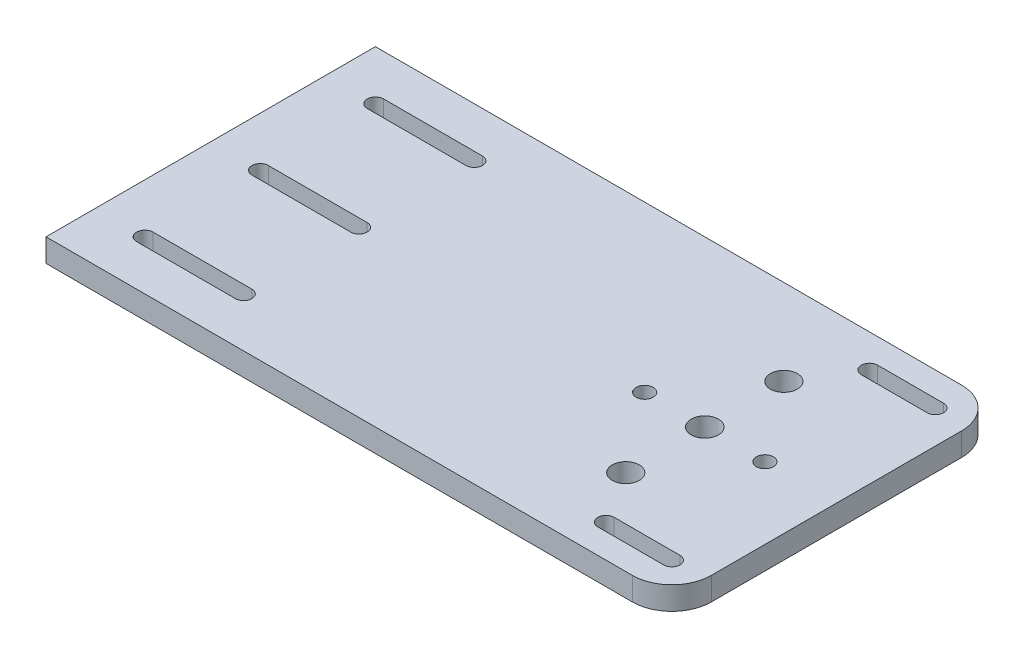
SolidWorks part; units mm, degrees
ref_plane "Front Plane" through (0, 0, 0) normal (0, 0, 1) x (1, 0, 0)
ref_plane "Top Plane" through (0, 0, 0) normal (0, 1, 0) x (1, 0, 0)
ref_plane "Right Plane" through (0, 0, 0) normal (1, 0, 0) x (0, 0, -1)
sketch "Sketch1" plane through (0, 0, 0) normal (0, 1, 0) x (1, 0, 0)
  line L0 (150, 0) -> (150, 100) construction
  line L1 (0, 0) -> (190, 0)
  line L2 (0, 0) -> (0, 100)
  line L3 (0, 100) -> (190, 100)
  line L4 (190, 0) -> (190, 100)
  line L5 (145.85, 50) -> (154.15, 50) construction
  line L9 (160, 10) -> (180, 10) construction
  line L10 (160, 12.5) -> (180, 12.5)
  line L11 (160, 7.5) -> (180, 7.5)
  line L14 (160, 90) -> (180, 90) construction
  line L15 (160, 87.5) -> (180, 87.5)
  line L16 (160, 92.5) -> (180, 92.5)
  line L20 (15, 85) -> (45, 85) construction
  line L21 (15, 87.5) -> (45, 87.5)
  line L22 (15, 82.5) -> (45, 82.5)
  line L23 (15, 50) -> (45, 50) construction
  line L24 (15, 52.5) -> (45, 52.5)
  line L25 (15, 47.5) -> (45, 47.5)
  line L26 (15, 15) -> (45, 15) construction
  line L29 (15, 17.5) -> (45, 17.5)
  line L30 (15, 12.5) -> (45, 12.5)
  line L48 (150, 50) -> (205, 50) construction
  circle A0 centre (150, 50) radius 4.15
  circle A1 centre (150, 74) radius 4.1
  circle A4 centre (131.75, 50) radius 2.6
  circle A6 centre (168.25, 50) radius 2.6
  arc A19 (15, 87.5) -> (15, 82.5) centre (15, 85) ccw
  arc A20 (45, 82.5) -> (45, 87.5) centre (45, 85) ccw
  arc A21 (15, 52.5) -> (15, 47.5) centre (15, 50) ccw
  arc A22 (45, 47.5) -> (45, 52.5) centre (45, 50) ccw
  arc A25 (15, 17.5) -> (15, 12.5) centre (15, 15) ccw
  arc A26 (45, 12.5) -> (45, 17.5) centre (45, 15) ccw
  circle A31 centre (150, 26) radius 4.1
  arc A36 (160, 12.5) -> (160, 7.5) centre (160, 10) ccw
  arc A37 (180, 7.5) -> (180, 12.5) centre (180, 10) ccw
  arc A38 (160, 87.5) -> (160, 92.5) centre (160, 90) cw
  arc A39 (180, 92.5) -> (180, 87.5) centre (180, 90) cw
  point P8 (150, 50)
  point P19 (170, 10)
  point P29 (170, 90)
  point P37 (30, 50)
  point P45 (30, 85)
  point P58 (30, 15)
  point P63 (150, 50)
  point P77 (0, 50)
  dimension "D4" = 8.3
  dimension "D5" = 8.2
  dimension "D6" = 5.2
  dimension "D15" = 15
  dimension "D19" = 2.5
  dimension "D11" = 7.5
  dimension "D9" = 2.5
  dimension "D1" = 190
  dimension "D2" = 100
  dimension "D3" = 40
  dimension "D7" = 24
  dimension "D8" = 18.25
  dimension "D10" = 20
  dimension "D12" = 10
  dimension "D20" = 30
  dimension "D21" = 15
  dimension "D22" = 15
  dimension "D24" = 50
extrude "Boss-Extrude1" add sketch "Sketch1" along normal blind 7
fillet "Fillet3" radius 12 2 edges at (190, 3.5, -100) (190, 3.5, 0)
